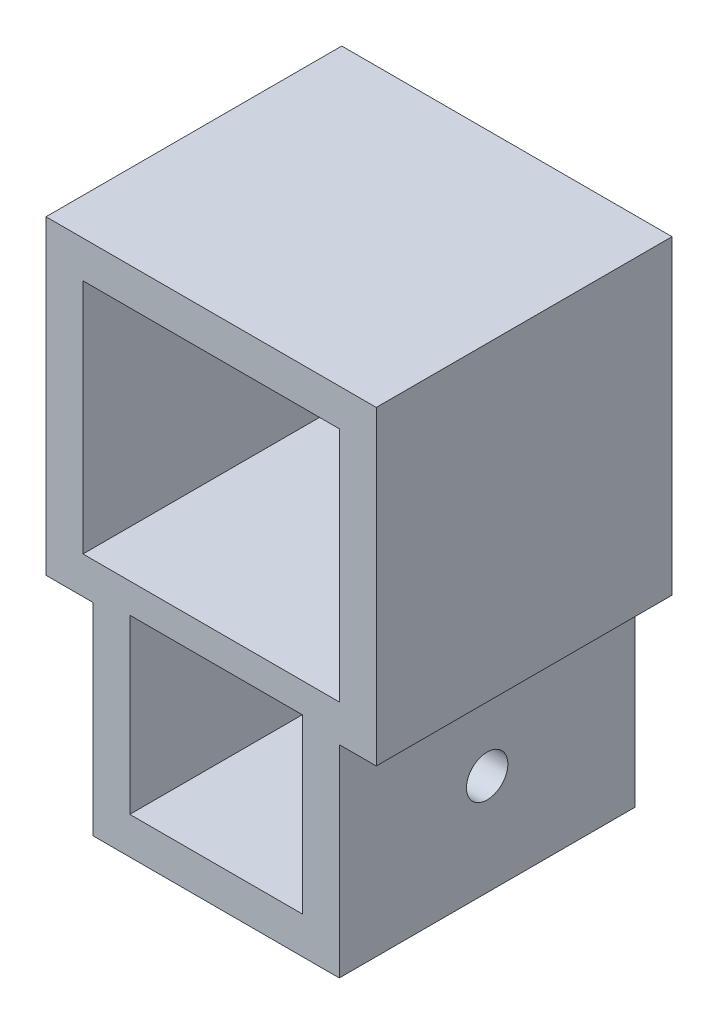
SolidWorks part; units mm, degrees
ref_plane "Plano frontal" through (0, 0, 0) normal (0, 0, 1) x (1, 0, 0)
ref_plane "Plano superior" through (0, 0, 0) normal (0, 1, 0) x (1, 0, 0)
ref_plane "Plano direito" through (0, 0, 0) normal (1, 0, 0) x (0, 0, -1)
sketch "Esboço1" plane through (0, 0, 0) normal (0, 0, 1) x (1, 0, 0)
  line L2 (-28.75, 15.4435) -> (-28.75, -5.0565)
  line L3 (-28.75, -5.0565) -> (-3.75, -5.0565)
  line L4 (-3.75, 15.4435) -> (-3.75, -5.0565)
  line L6 (-25, 15.4435) -> (-25, -1.3065)
  line L7 (-25, -1.3065) -> (-7.5, -1.3065)
  line L8 (-7.5, 15.4435) -> (-7.5, -1.3065)
  line L9 (-28.75, 15.4435) -> (-33.5, 15.4435)
  line L14 (-33.5, 15.4435) -> (-33.5, 46.9435)
  line L15 (-33.5, 46.9435) -> (0, 46.9435)
  line L16 (0, 46.9435) -> (0, 15.4435)
  line L17 (0, 15.4435) -> (-3.75, 15.4435)
  line L18 (-25, 15.4435) -> (-25, 16.1935)
  line L19 (-25, 19.1935) -> (-29.75, 19.1935)
  line L20 (-29.75, 19.1935) -> (-29.75, 43.1935)
  line L21 (-29.75, 43.1935) -> (-3.75, 43.1935)
  line L22 (-3.75, 43.1935) -> (-3.75, 19.1935)
  line L23 (-3.75, 19.1935) -> (-7.5, 19.1935)
  line L24 (-7.5, 16.1935) -> (-7.5, 15.4435)
  line L25 (-25, 19.1935) -> (-7.5, 19.1935)
  line L26 (-25, 16.1935) -> (-7.5, 16.1935)
  dimension "D1" = 25
  dimension "D2" = 17.5
  dimension "D3" = 3.75
  dimension "D4" = 3.75
  dimension "D5" = 20.5
  dimension "D6" = 33.5
  dimension "D7" = 3.75
  dimension "D8" = 31.5
  dimension "D9" = 3.75
  dimension "D10" = 3.75
  dimension "D11" = 3.75
  dimension "D12" = 20.5
  dimension "D13" = 33.5
  dimension "D14" = 3
extrude "Ressalto-extrusão2" add sketch "Esboço1" along normal blind 30
sketch "Esboço2" plane through (-28.75, 0, 0) normal (-1, 0, 0) x (0, 0, 1)
  line L0 (0, 15.4435) -> (0, -5.0565) construction
  circle A0 centre (15, 5.1935) radius 2.1
  dimension "D2" = 4.2
  dimension "D1" = 15
extrude "Corte-extrusão1" cut sketch "Esboço2" against normal through all
